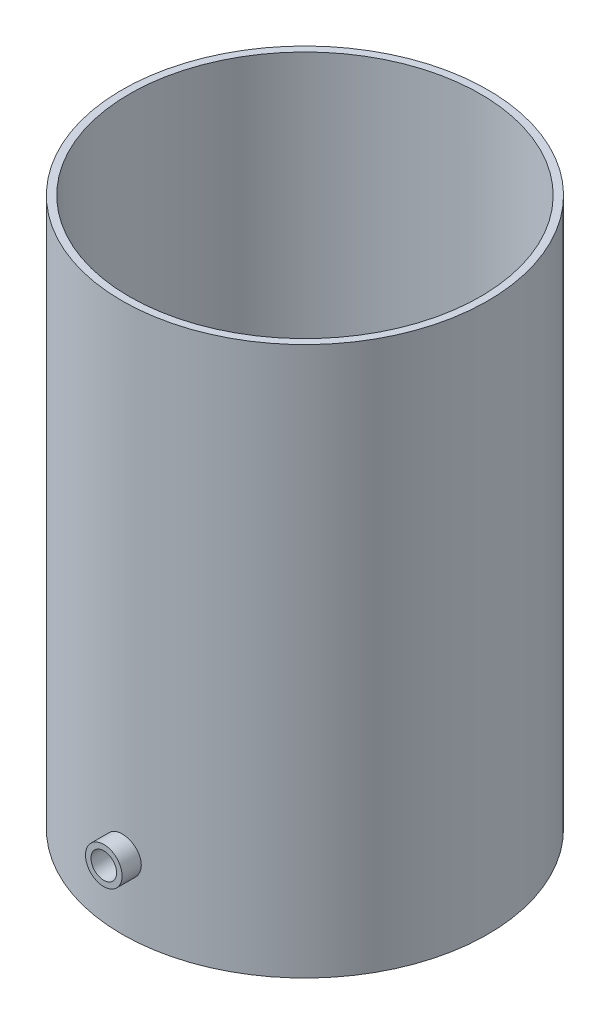
SolidWorks part; units mm, degrees
ref_plane "Front Plane" through (0, 0, 0) normal (0, 0, 1) x (1, 0, 0)
ref_plane "Top Plane" through (0, 0, 0) normal (0, 1, 0) x (1, 0, 0)
ref_plane "Right Plane" through (0, 0, 0) normal (1, 0, 0) x (0, 0, -1)
sketch "Sketch1" plane through (0, 0, 0) normal (0, 1, 0) x (1, 0, 0)
  circle A0 centre (0, 0) radius 50
  circle A1 centre (0, 0) radius 48
extrude "Boss-Extrude2" add sketch "Sketch1" along normal blind 150
ref_plane "Plane1" through (0, 0, 55) normal (0, 0, 1) x (1, 0, 0)
sketch "Sketch2" plane through (0, 0, 55) normal (0, 0, 1) x (1, 0, 0)
  circle A0 centre (0, 18.7906) radius 5
extrude "Boss-Extrude3" add sketch "Sketch2" against normal up to surface (5.2506 mm away)
sketch "Sketch3" plane through (0, 0, 55) normal (0, 0, 1) x (1, 0, 0)
  circle A0 centre (0, 18.7906) radius 3.5
extrude "Cut-Extrude1" cut sketch "Sketch3" against normal blind 12
ref_plane "Plane2" through (0, 0, -55) normal (0, 0, 1) x (1, 0, 0)
sketch "Sketch4" plane through (0, 0, -55) normal (0, 0, 1) x (1, 0, 0)
  circle A0 centre (0, 18.7906) radius 5
extrude "Boss-Extrude4" add sketch "Sketch4" along normal up to surface (5.2506 mm away)
sketch "Sketch5" plane through (0, 0, -55) normal (0, 0, -1) x (-1, 0, 0)
  circle A0 centre (0, 18.7906) radius 3.5
extrude "Cut-Extrude2" cut sketch "Sketch5" against normal blind 12
